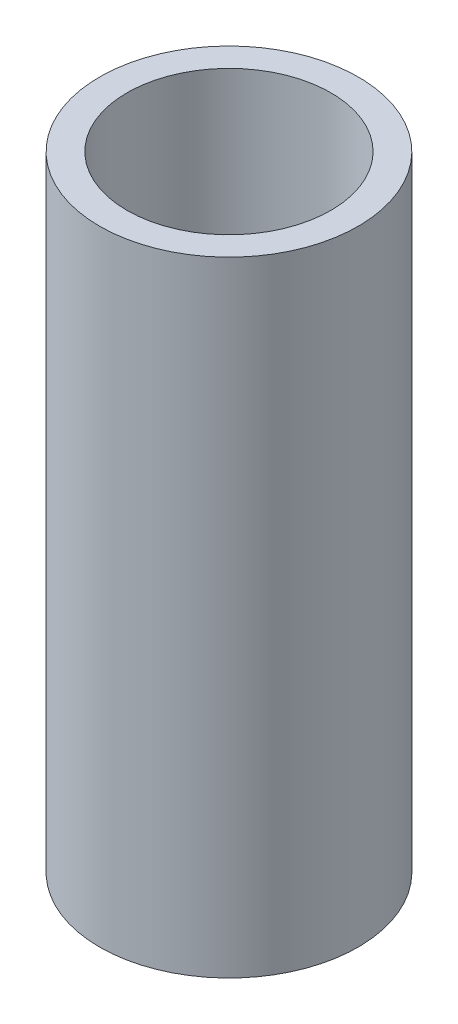
SolidWorks part; units mm, degrees
material "PVC 0.007 Plastificado"
ref_plane "Alzado" through (0, 0, 0) normal (0, 0, 1) x (1, 0, 0)
ref_plane "Planta" through (0, 0, 0) normal (0, 1, 0) x (1, 0, 0)
ref_plane "Vista lateral" through (0, 0, 0) normal (1, 0, 0) x (0, 0, -1)
sketch "Croquis1" plane through (0, 0, 0) normal (0, 1, 0) x (1, 0, 0)
  circle A0 centre (0, 0) radius 14.5
  circle A1 centre (0, 0) radius 11.43
  dimension "D1" = 29
  dimension "D2" = 22.86
extrude "Saliente-Extruir1" add sketch "Croquis1" along normal mid plane 70
